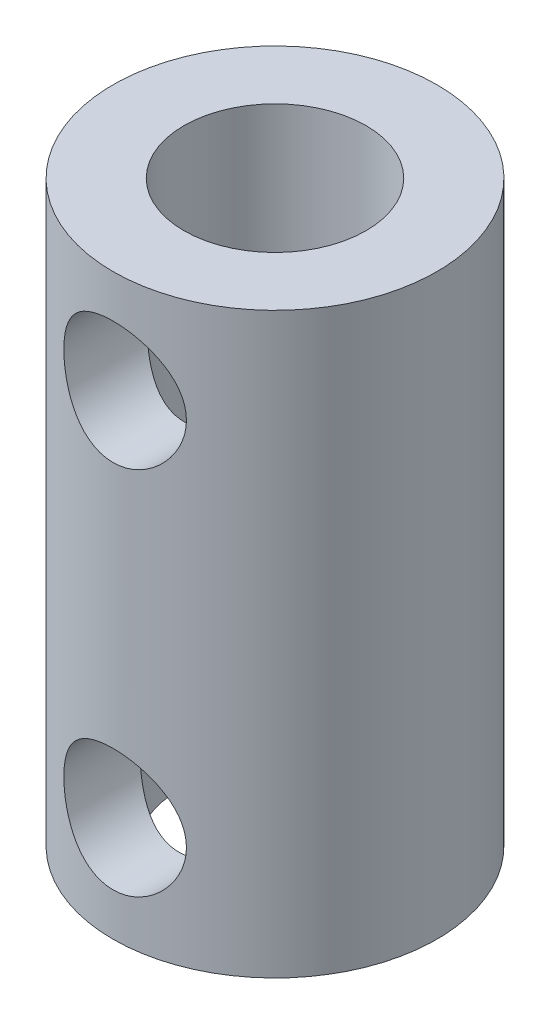
SolidWorks part; units mm, degrees
ref_plane "Front Plane" through (0, 0, 0) normal (0, 0, 1) x (1, 0, 0)
ref_plane "Top Plane" through (0, 0, 0) normal (0, 1, 0) x (1, 0, 0)
ref_plane "Right Plane" through (0, 0, 0) normal (1, 0, 0) x (0, 0, -1)
sketch "Sketch1" plane through (0, 0, 0) normal (0, 0, 1) x (1, 0, 0)
  line L0 (5.334, 19.05) -> (0, 19.05)
  line L1 (0, 19.05) -> (0, 0)
  line L2 (0, 0) -> (5.334, 0)
  line L3 (5.334, 0) -> (5.334, 19.05)
  line L4 (0, 19.05) -> (0, 0) construction
revolve "Revolve1" add sketch "Sketch1" angle 360 about L4
hole_wizard "Hole1" positions "Sketch3" profile "Sketch2" legacy
sketch "Sketch3" plane through (0, 0, 0) normal (0, -1, 0) x (-1, 0, 0)
  point P0 (0, 0)
sketch "Sketch2" plane through (0, 0, 0) normal (1, 0, 0) x (0, 0, -1)
  line L0 (0, 0) -> (0, 19.05)
  line L1 (0, 19.05) -> (3, 19.05)
  line L2 (3, 19.05) -> (3, 9.6302)
  line L3 (3, 9.6302) -> (3.175, 9.525)
  line L4 (3.175, 9.525) -> (3.175, 0)
  line L5 (3.175, 0) -> (0, 0)
  line L6 (0, -6.13) -> (0, 109.2824) construction
  line L7 (-3, 9.6302) -> (-3.175, 9.525) construction
  line L8 (0, 19.05) -> (-3, 19.05) construction
  dimension "Diameter" = 6
  dimension "Depth" = 19.05
  dimension "C-Drill Diameter" = 6.35
  dimension "C-Drill Depth" = 9.525
  dimension "C-Drill Angle" = 118
hole_wizard "M3.5 Clearance Hole1" positions "3DSketch1" profile "Sketch4" hole size "M3.5" standard "ANSI Metric"
sketch3d "3DSketch1"
  point P0 (0, 15.621, 5.334)
sketch "Sketch4" plane through (0, 15.621, 5.334) normal (1, 0, 0) x (0, -1, 0)
  line L0 (0, 0) -> (0, 2.334)
  line L1 (0, 2.334) -> (2.0193, 2.334)
  line L2 (2.0193, 2.334) -> (2.0193, 0)
  line L5 (2.0193, 0) -> (0, 0)
  line L11 (0, -6.35) -> (0, 107.95) construction
  dimension "Thru Hole Dia." = 4.0386
  dimension "Thru Hole Depth" = 2.334
hole_wizard "M3.5 Clearance Hole2" positions "3DSketch2" profile "Sketch5" hole size "M3.5" standard "ANSI Metric"
sketch3d "3DSketch2"
  point P0 (0, 3.429, 5.334)
sketch "Sketch5" plane through (0, 3.429, 5.334) normal (1, 0, 0) x (0, -1, 0)
  line L0 (0, 0) -> (0, 2.159)
  line L1 (0, 2.159) -> (2.0193, 2.159)
  line L2 (2.0193, 2.159) -> (2.0193, 0)
  line L5 (2.0193, 0) -> (0, 0)
  line L11 (0, -6.35) -> (0, 107.95) construction
  dimension "Thru Hole Dia." = 4.0386
  dimension "Thru Hole Depth" = 2.159
